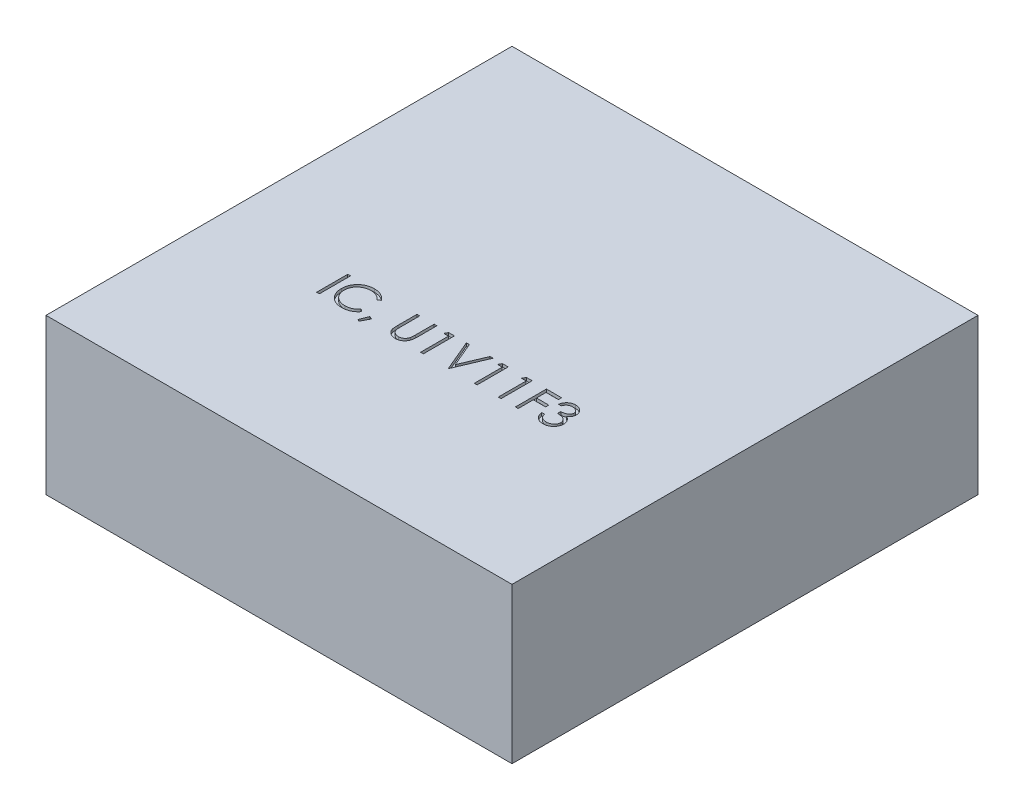
SolidWorks part; units mm, degrees
ref_plane "Front Plane" through (0, 0, 0) normal (0, 0, 1) x (1, 0, 0)
ref_plane "Top Plane" through (0, 0, 0) normal (0, 1, 0) x (1, 0, 0)
ref_plane "Right Plane" through (0, 0, 0) normal (1, 0, 0) x (0, 0, -1)
sketch "BaseS" plane through (0, 0, 0) normal (0, 1, 0) x (1, 0, 0)
  line L1 (-1.5, 1.5) -> (1.5, 1.5)
  line L2 (-1.5, 1.5) -> (-1.5, -1.5)
  line L3 (-1.5, -1.5) -> (1.5, -1.5)
  line L4 (1.5, 1.5) -> (1.5, -1.5)
  line L5 (-1.5, 1.5) -> (1.5, -1.5) construction
  line L6 (-1.5, -1.5) -> (1.5, 1.5) construction
  point P0 (0, 0)
  dimension "Dim" = 3
extrude "Base" add sketch "BaseS" along normal blind 1
sketch "PartNumberS" plane through (0, 1, 0) normal (0, 1, 0) x (1, 0, 0)
  line L0 (1.5, -0.5) -> (-1.5, -0.5) construction
  line L3 (-1.5, -1.5) -> (1.5, -1.5) construction
  line L4 (-1.5, 1.5) -> (-1.5, -1.5) construction
  line L5 (1.5, -1.5) -> (1.5, 1.5) construction
  text T0 "IC, U1V11F3" font "Century Gothic" height 0.2
  point P2 (-1.7832, 3.5)
  point P3 (-1.5, -0.5)
  point P9 (1.43, -0.5)
  point P11 (1.5, -0.5)
  dimension "YDim" = 1
extrude "PartNumber" cut sketch "PartNumberS" against normal blind 0.02
